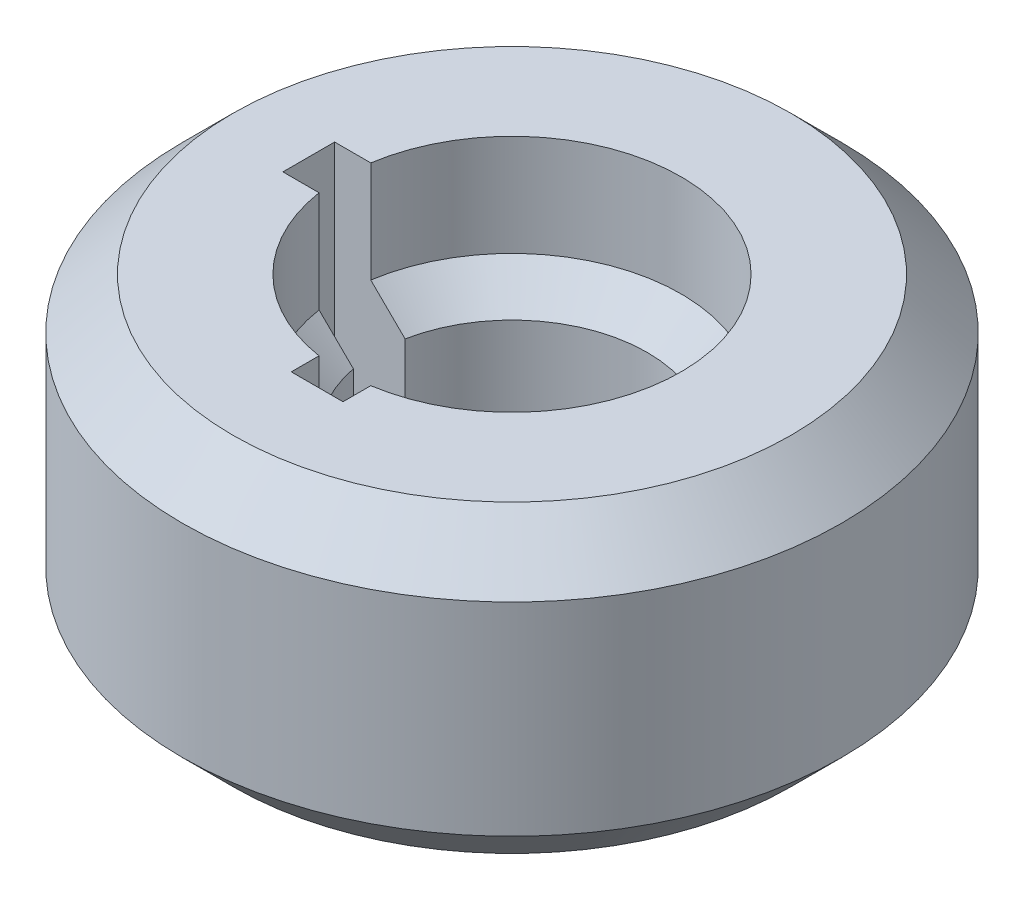
SolidWorks part; units mm, degrees
ref_plane "Front Plane" through (0, 0, 0) normal (0, 0, 1) x (1, 0, 0)
ref_plane "Top Plane" through (0, 0, 0) normal (0, 1, 0) x (1, 0, 0)
ref_plane "Right Plane" through (0, 0, 0) normal (1, 0, 0) x (0, 0, -1)
sketch "Sketch2" plane through (0, 0, 0) normal (0, 0, 1) x (1, 0, 0)
  line L0 (0, 25) -> (0, -25) construction
  line L1 (-16, -24.6703) -> (-39, -24.6703)
  line L2 (-39, -24.6703) -> (-39, 11.3297)
  line L3 (-39, 11.3297) -> (-20, 11.3297)
  line L4 (-20, 11.3297) -> (-20, -0.6703)
  line L5 (-20, -0.6703) -> (-16, -4.6703)
  line L6 (-16, -4.6703) -> (-16, -24.6703)
  point P3 (0, 0)
  dimension "D1" = 19
  dimension "D2" = 23
  dimension "D3" = 36
  dimension "D4" = 20
  dimension "D5" = 24
  dimension "D6" = 20
revolve "Revolve2" add sketch "Sketch2" angle 360 about L0
chamfer "Chamfer2" distance 6 angle 45 1 edges at (-39, -24.6703, 0)
sketch "Sketch8" plane through (0, 0, 0) normal (0, 1, 0) x (1, 0, 0)
  line L1 (-3.06, 0) -> (3.06, 0)
  line L2 (-3.06, 0) -> (-3.06, -23.05)
  line L3 (-3.06, -23.05) -> (3.06, -23.05)
  line L4 (3.06, 0) -> (3.06, -23.05)
  line L5 (0, 3.06) -> (-24.04, 3.06)
  line L6 (0, 3.06) -> (0, -3.06)
  line L7 (0, -3.06) -> (-24.04, -3.06)
  line L8 (-24.04, 3.06) -> (-24.04, -3.06)
  point P4 (0, 0)
  point P10 (0, 0)
  point P11 (0, 0)
extrude "Cut-Extrude2" cut sketch "Sketch8" against normal mid plane 58 contours L6 L7 L2 L3 L4 L1 | L5 L8 L7 L2 L1 L6
chamfer "Chamfer5" distance 6 angle 45 1 edges at (-39, 11.3297, 0)
